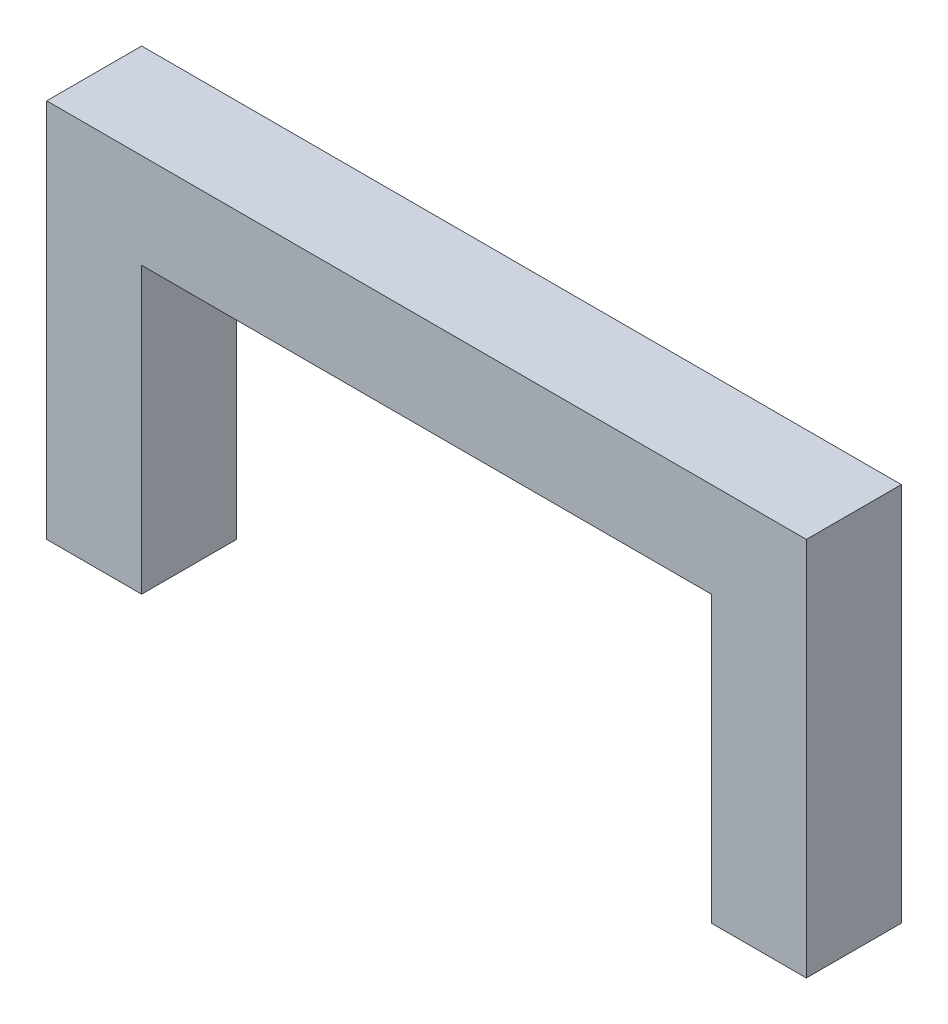
SolidWorks part; units mm, degrees
ref_plane "Front" through (0, 0, 0) normal (0, 0, 1) x (1, 0, 0)
ref_plane "Top" through (0, 0, 0) normal (0, 1, 0) x (1, 0, 0)
ref_plane "Right" through (0, 0, 0) normal (1, 0, 0) x (0, 0, -1)
sketch "Sketch2" plane through (0, 0, 0) normal (0, 0, 1) x (1, 0, 0)
  line L1 (-46.8509, 10.8152) -> (54.7491, 10.8152)
  line L2 (-46.8509, 10.8152) -> (-46.8509, -39.9848)
  line L3 (-46.8509, -39.9848) -> (54.7491, -39.9848)
  line L4 (54.7491, 10.8152) -> (54.7491, -39.9848)
  line L5 (-34.1509, -39.9848) -> (42.0491, -39.9848)
  line L6 (-34.1509, -39.9848) -> (-34.1509, -1.8848)
  line L7 (-34.1509, -1.8848) -> (42.0491, -1.8848)
  line L8 (42.0491, -39.9848) -> (42.0491, -1.8848)
  dimension "D1" = 50.8
  dimension "D2" = 101.6
  dimension "D3" = 12.7
  dimension "D4" = 12.7
  dimension "D5" = 12.7
extrude "Boss-Extrude1" add sketch "Sketch2" along normal blind 12.7 contours L8 L3 L4 L1 L2 L6 L7
